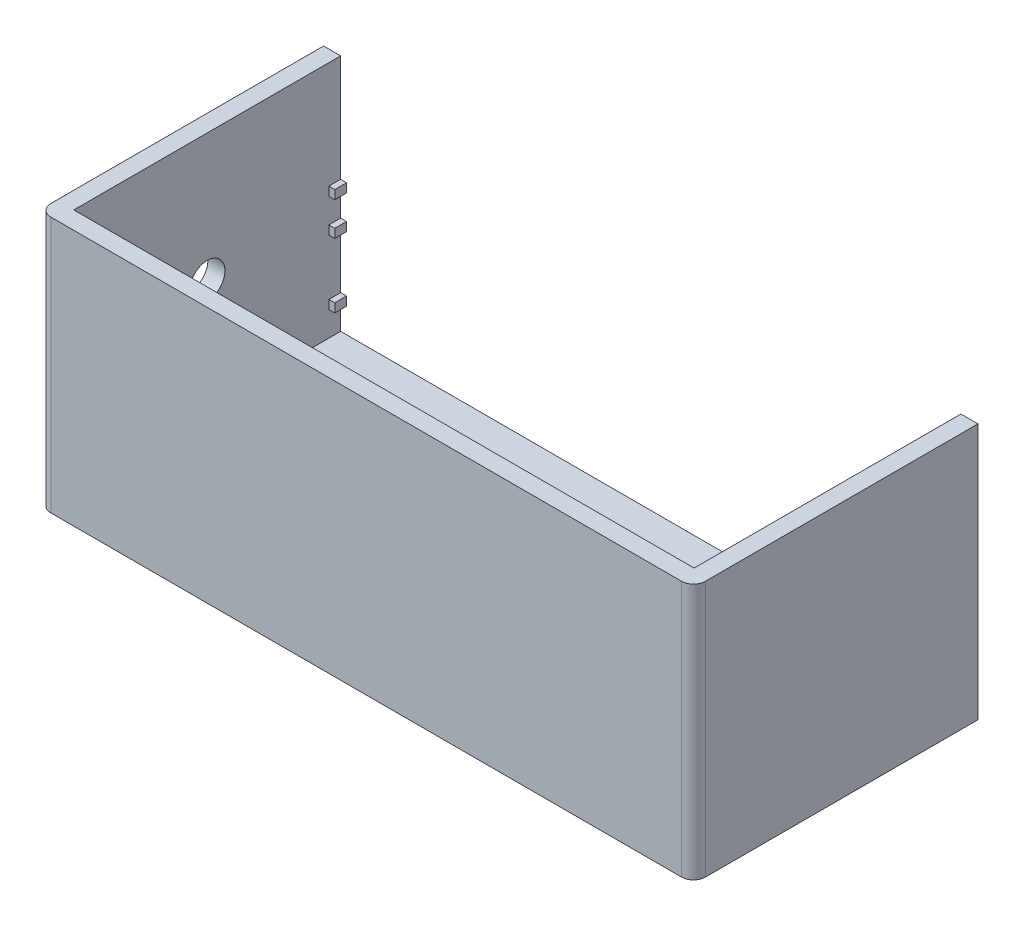
SolidWorks part; units mm, degrees
ref_plane "Front Plane" through (0, 0, 0) normal (0, 0, 1) x (1, 0, 0)
ref_plane "Top Plane" through (0, 0, 0) normal (0, 1, 0) x (1, 0, 0)
ref_plane "Right Plane" through (0, 0, 0) normal (1, 0, 0) x (0, 0, -1)
sketch "Sketch1" plane through (0, 0, 0) normal (0, 1, 0) x (1, 0, 0)
  line L1 (55.55, -25.65) -> (-55.55, -25.65)
  line L2 (55.55, -25.65) -> (55.55, 25.65)
  line L3 (55.55, 25.65) -> (-55.55, 25.65)
  line L4 (-55.55, -25.65) -> (-55.55, 25.65)
  line L5 (55.55, -25.65) -> (-55.55, 25.65) construction
  line L6 (55.55, 25.65) -> (-55.55, -25.65) construction
  point P0 (0, 0)
  dimension "D1" = 111.1
  dimension "D2" = 51.3
extrude "Boss-Extrude1" add sketch "Sketch1" along normal blind 3
sketch "Sketch2" plane through (0, 3, 0) normal (0, 1, 0) x (1, 0, 0)
  line L1 (52.65, -22.65) -> (-52.65, -22.65)
  line L2 (52.65, -22.65) -> (52.65, 22.65)
  line L3 (52.65, 22.65) -> (-52.65, 22.65)
  line L4 (-52.65, -22.65) -> (-52.65, 22.65)
  line L5 (52.65, -22.65) -> (-52.65, 22.65) construction
  line L6 (52.65, 22.65) -> (-52.65, -22.65) construction
  line L7 (55.55, 25.65) -> (-55.55, 25.65)
  line L8 (55.55, 25.65) -> (55.55, -25.65)
  line L9 (55.55, -25.65) -> (-55.55, -25.65)
  line L10 (-55.55, 25.65) -> (-55.55, -25.65)
  line L11 (55.55, 25.65) -> (-55.55, -25.65) construction
  line L12 (55.55, -25.65) -> (-55.55, 25.65) construction
  point P0 (0, 0)
  point P6 (0, 0)
  dimension "D1" = 105.3
  dimension "D2" = 45.3
extrude "Boss-Extrude2" add sketch "Sketch2" along normal blind 40.5
sketch "Sketch5" plane through (0, 0, -25.65) normal (0, 0, -1) x (-1, 0, 0)
  line L0 (0, 43.5) -> (0, 0) construction
  line L1 (-55.55, 43.5) -> (55.55, 43.5) construction
  line L2 (-55.55, 43.5) -> (0, 43.5) construction
  line L3 (-27.775, 43.5) -> (-27.775, 0) construction
  line L4 (-55.55, 0) -> (55.55, 0) construction
  circle A0 centre (-27.775, 21.75) radius 21
  circle A1 centre (27.775, 21.75) radius 21
  dimension "D1" = 42
extrude "Boss-Extrude4" add sketch "Sketch5" along normal blind 15
sketch "Sketch6" plane through (0, 0, -40.65) normal (0, 0, -1) x (-1, 0, 0)
  line L0 (-27.775, 42.75) -> (-27.775, 0.75) construction
  line L1 (27.775, 42.75) -> (27.775, 0.75) construction
  line L3 (-20.025, 3.25) -> (-35.525, 3.25)
  line L4 (-20.025, 3.25) -> (-20.025, 40.25)
  line L5 (-20.025, 40.25) -> (-35.525, 40.25)
  line L6 (-35.525, 3.25) -> (-35.525, 40.25)
  line L7 (-20.025, 3.25) -> (-35.525, 40.25) construction
  line L8 (-20.025, 40.25) -> (-35.525, 3.25) construction
  line L9 (35.525, 3.25) -> (20.025, 3.25)
  line L10 (35.525, 3.25) -> (35.525, 40.25)
  line L11 (35.525, 40.25) -> (20.025, 40.25)
  line L12 (20.025, 3.25) -> (20.025, 40.25)
  line L13 (35.525, 3.25) -> (20.025, 40.25) construction
  line L14 (35.525, 40.25) -> (20.025, 3.25) construction
  circle A0 centre (-27.775, 21.75) radius 21 construction
  circle A1 centre (-27.775, 21.75) radius 21 construction
  circle A2 centre (27.775, 21.75) radius 21 construction
  circle A3 centre (27.775, 21.75) radius 21 construction
  point P14 (-27.775, 21.75)
  point P19 (27.775, 21.75)
  dimension "D1" = 15.5
  dimension "D2" = 37
extrude "Cut-Extrude1" cut sketch "Sketch6" against normal blind 21
sketch "Sketch8" plane through (0, 0, -40.65) normal (0, 0, -1) x (-1, 0, 0)
  line L0 (-27.775, 42.75) -> (-27.775, 0.75) construction
  line L2 (-21.625, 4.6) -> (-33.925, 4.6)
  line L3 (-21.625, 4.6) -> (-21.625, 38.9)
  line L4 (-21.625, 38.9) -> (-33.925, 38.9)
  line L5 (-33.925, 4.6) -> (-33.925, 38.9)
  line L6 (-21.625, 4.6) -> (-33.925, 38.9) construction
  line L7 (-21.625, 38.9) -> (-33.925, 4.6) construction
  circle A0 centre (-27.775, 21.75) radius 21 construction
  circle A1 centre (-27.775, 21.75) radius 21 construction
  circle A2 centre (-27.775, 21.75) radius 21
  dimension "D1" = 12.3
  dimension "D2" = 34.3
extrude "Boss-Extrude5" add sketch "Sketch8" against normal blind 1
sketch "Sketch9" plane through (0, 0, -40.65) normal (0, 0, -1) x (-1, 0, 0)
  line L0 (27.775, 42.75) -> (27.775, 0.75) construction
  line L2 (33.925, 4.6) -> (21.625, 4.6)
  line L3 (33.925, 4.6) -> (33.925, 38.9)
  line L4 (33.925, 38.9) -> (21.625, 38.9)
  line L5 (21.625, 4.6) -> (21.625, 38.9)
  line L6 (33.925, 4.6) -> (21.625, 38.9) construction
  line L7 (33.925, 38.9) -> (21.625, 4.6) construction
  circle A0 centre (27.775, 21.75) radius 21 construction
  circle A1 centre (27.775, 21.75) radius 21 construction
  circle A2 centre (27.775, 21.75) radius 21
  point P7 (27.775, 21.75)
  dimension "D1" = 12.3
  dimension "D2" = 34.3
extrude "Boss-Extrude6" add sketch "Sketch9" against normal blind 1
sketch "Sketch10" plane through (0, 0, -22.65) normal (0, 0, 1) x (1, 0, 0)
  line L0 (0, 43.5) -> (0, 0) construction
  line L1 (-55.55, 43.5) -> (55.55, 43.5) construction
  line L3 (63.1223, -12.5986) -> (-63.1223, -12.5986)
  line L4 (63.1223, -12.5986) -> (63.1223, 56.0986)
  line L5 (63.1223, 56.0986) -> (-63.1223, 56.0986)
  line L6 (-63.1223, -12.5986) -> (-63.1223, 56.0986)
  line L7 (63.1223, -12.5986) -> (-63.1223, 56.0986) construction
  line L8 (63.1223, 56.0986) -> (-63.1223, -12.5986) construction
  point P5 (0, 21.75)
extrude "Cut-Extrude3" cut sketch "Sketch10" against normal blind 53
sketch "Sketch12" plane through (0, 0, -22.65) normal (0, 0, -1) x (-1, 0, 0)
  line L0 (52.65, 8.7) -> (51.65, 8.7)
  line L1 (52.65, 43.5) -> (52.65, 3) construction
  line L2 (51.65, 8.7) -> (51.65, 7.2)
  line L3 (51.65, 7.2) -> (52.65, 7.2)
  line L4 (0, 43.5) -> (0, 0) construction
  line L5 (52.65, 43.5) -> (-52.65, 43.5) construction
  line L6 (0, 21.75) -> (55.55, 21.75) construction
  line L7 (55.55, 43.5) -> (55.55, 0) construction
  line L8 (52.65, 25.35) -> (51.65, 25.35)
  line L9 (51.65, 25.35) -> (51.65, 23.85)
  line L10 (51.65, 23.85) -> (52.65, 23.85)
  line L11 (52.65, 23.85) -> (52.65, 25.35)
  line L12 (52.65, 19.65) -> (52.65, 18.15)
  line L13 (51.65, 19.65) -> (52.65, 19.65)
  line L14 (51.65, 18.15) -> (51.65, 19.65)
  line L15 (52.65, 18.15) -> (51.65, 18.15)
  line L16 (52.65, 3) -> (-52.65, 3) construction
  line L18 (-51.65, 7.2) -> (-52.65, 7.2)
  line L19 (-51.65, 8.7) -> (-51.65, 7.2)
  line L20 (-52.65, 8.7) -> (-51.65, 8.7)
  line L21 (-52.65, 19.65) -> (-52.65, 18.15)
  line L22 (-52.65, 18.15) -> (-51.65, 18.15)
  line L23 (-51.65, 18.15) -> (-51.65, 19.65)
  line L24 (-51.65, 19.65) -> (-52.65, 19.65)
  line L25 (-52.65, 23.85) -> (-52.65, 25.35)
  line L26 (-51.65, 23.85) -> (-52.65, 23.85)
  line L27 (-51.65, 25.35) -> (-51.65, 23.85)
  line L28 (-52.65, 25.35) -> (-51.65, 25.35)
  line L29 (-52.65, 25.35) -> (-52.65, 23.85)
  line L30 (-52.65, 19.65) -> (-52.65, 18.15)
  line L31 (-52.65, 8.7) -> (-52.65, 7.2)
  line M15 (52.65, 43.5) -> (52.65, 3)
  line M17 (-52.65, 3) -> (-52.65, 43.5)
  dimension "D1" = 1
  dimension "D2" = 1.5
  dimension "D3" = 2.1
  dimension "D4" = 4.2
extrude "Boss-Extrude8" add sketch "Sketch12" against normal blind 2 contours L15 L13 L14 M15 | L2 L3 L0 M15 | L23 L24 L22 M17 | L28 L26 L27 M17 | L9 L10 L11 L8 | L19 L18 L31 L20
fillet "Fillet1" radius 2 2 edges at (-55.55, 21.75, 25.65) (55.55, 21.75, 25.65)
sketch "Sketch13" plane through (-52.65, 0, 0) normal (1, 0, 0) x (0, 0, -1)
  line L0 (0, 0) -> (0, 43.5) construction
  line L1 (-23.65, 43.5) -> (22.65, 43.5) construction
  circle A0 centre (0, 21.75) radius 3
  dimension "D1" = 6
extrude "Cut-Extrude4" cut sketch "Sketch13" against normal blind 14
